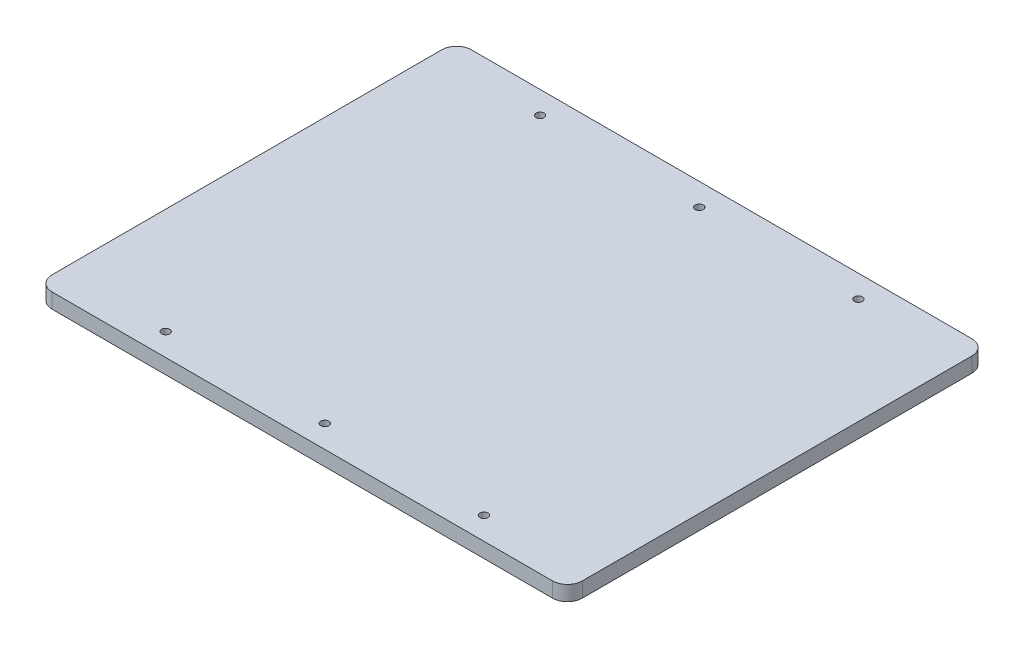
SolidWorks part; units mm, degrees
material "Acrylic (Medium-high impact)"
ref_plane "Front Plane" through (0, 0, 0) normal (0, 0, 1) x (1, 0, 0)
ref_plane "Top Plane" through (0, 0, 0) normal (0, 1, 0) x (1, 0, 0)
ref_plane "Right Plane" through (0, 0, 0) normal (1, 0, 0) x (0, 0, -1)
sketch "Sketch1" plane through (0, 0, 0) normal (0, 1, 0) x (1, 0, 0)
  line L0 (0, 79.375) -> (0, 64.8821) construction
  line L1 (112.395, 88.9) -> (-112.395, 88.9) construction
  line L2 (112.395, 88.9) -> (112.395, -88.9) construction
  line L3 (112.395, -88.9) -> (-112.395, -88.9) construction
  line L4 (-112.395, 88.9) -> (-112.395, -88.9) construction
  line L5 (0, 0) -> (112.395, 0) construction
  line L6 (-112.395, 82.55) -> (-112.395, 44.45) construction
  line L7 (-112.395, 44.45) -> (-113.792, 44.45) construction
  line L8 (-113.792, 44.45) -> (-113.792, 63.5) construction
  line L9 (-107.442, 69.85) -> (-62.1983, 69.85) construction
  line L10 (-55.8482, 63.5) -> (-55.8483, 44.45) construction
  line L11 (-55.8483, 44.45) -> (-57.2452, 44.45) construction
  line L12 (-57.2452, 44.45) -> (-57.2452, 63.5) construction
  line L13 (-50.8952, 69.85) -> (-5.6515, 69.85) construction
  line L14 (0.6985, 63.5) -> (0.6985, 44.45) construction
  line L15 (0.6985, 44.45) -> (-0.6985, 44.45) construction
  line L16 (-0.6985, 44.45) -> (-0.6985, 63.5) construction
  line L17 (5.6515, 69.85) -> (50.8952, 69.85) construction
  line L18 (113.792, 63.5) -> (113.792, 44.45) construction
  line L19 (113.792, 44.45) -> (112.395, 44.45) construction
  line L20 (112.395, 44.45) -> (112.395, 82.55) construction
  line L21 (106.045, 88.9) -> (-106.045, 88.9) construction
  line L22 (57.2452, 63.5) -> (57.2452, 44.45) construction
  line L23 (57.2452, 44.45) -> (55.8483, 44.45) construction
  line L24 (55.8483, 44.45) -> (55.8482, 63.5) construction
  line L25 (62.1983, 69.85) -> (107.442, 69.85) construction
  line L26 (0, 44.45) -> (0, 64.8821) construction
  line L27 (-106.045, 82.55) -> (-106.045, 88.9) construction
  line L28 (0, 0) -> (-65.7701, 0) construction
  line L29 (-103.8701, 63.5) -> (-65.7701, 63.5) construction
  line L30 (-103.8701, 63.5) -> (-103.8701, -63.5) construction
  line L31 (-103.8701, -63.5) -> (-65.7701, -63.5) construction
  line L32 (-65.7701, 63.5) -> (-65.7701, -63.5) construction
  line L33 (-84.8201, 63.5) -> (-84.8201, 69.85) construction
  line L34 (-103.8701, 63.5) -> (-113.792, 63.5) construction
  line L35 (112.395, 79.375) -> (-112.395, 79.375) construction
  line L36 (-28.2734, 69.85) -> (-28.2734, 79.375) construction
  line L37 (-28.2734, 79.375) -> (-28.2734, 88.9) construction
  line L42 (-106.045, 88.9) -> (106.045, 88.9)
  line L43 (-112.395, 82.55) -> (-112.395, -82.55)
  line L44 (-106.045, -88.9) -> (106.045, -88.9)
  line L45 (112.395, 82.55) -> (112.395, -82.55)
  arc A0 (107.442, 69.85) -> (113.792, 63.5) centre (107.442, 63.5) cw construction
  arc A1 (106.045, 88.9) -> (112.395, 82.55) centre (106.045, 82.55) cw construction
  arc A2 (-106.045, 88.9) -> (-112.395, 82.55) centre (-106.045, 82.55) ccw construction
  arc A3 (62.1983, 69.85) -> (55.8482, 63.5) centre (62.1983, 63.5) ccw construction
  arc A4 (50.8952, 69.85) -> (57.2452, 63.5) centre (50.8952, 63.5) cw construction
  arc A5 (5.6515, 69.85) -> (-0.6985, 63.5) centre (5.6515, 63.5) ccw construction
  arc A6 (-5.6515, 69.85) -> (0.6985, 63.5) centre (-5.6515, 63.5) cw construction
  arc A7 (-50.8952, 69.85) -> (-57.2452, 63.5) centre (-50.8952, 63.5) ccw construction
  arc A8 (-62.1983, 69.85) -> (-55.8482, 63.5) centre (-62.1983, 63.5) cw construction
  arc A9 (-107.442, 69.85) -> (-113.792, 63.5) centre (-107.442, 63.5) ccw construction
  circle A10 centre (-67.47, 79.375) radius 1.7
  circle A11 centre (0, 79.375) radius 1.7
  circle A12 centre (67.4688, 79.375) radius 1.7
  circle A13 centre (67.4688, -79.375) radius 1.7
  circle A14 centre (0, -79.375) radius 1.7
  circle A15 centre (-67.47, -79.375) radius 1.7
  arc A16 (-112.395, -82.55) -> (-106.045, -88.9) centre (-106.045, -82.55) ccw
  arc A17 (112.395, -82.55) -> (106.045, -88.9) centre (106.045, -82.55) cw
  arc A18 (112.395, 82.55) -> (106.045, 88.9) centre (106.045, 82.55) ccw
  arc A19 (-106.045, 88.9) -> (-112.395, 82.55) centre (-106.045, 82.55) ccw
  point P0 (0, 0)
  point P58 (-55.8483, 69.85)
  point P61 (-113.792, 69.85)
  dimension "D8" = 6.35
  dimension "D10" = 3.4
  dimension "D3" = 6.35
  dimension "D1" = 6.35
  dimension "D2" = 224.79
  dimension "D4" = 45.2437
  dimension "D5" = 19.05
  dimension "D6" = 38.1
  dimension "D7" = 127
  dimension "D9" = 44.45
  dimension "D11" = 67.47
  dimension "D12" = 67.4688
extrude "Boss-Extrude1" add sketch "Sketch1" along normal blind 6.35
